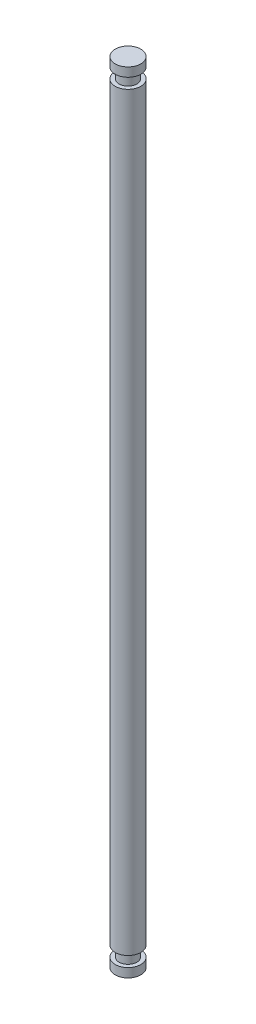
SolidWorks part; units mm, degrees
ref_plane "Front Plane" through (0, 0, 0) normal (1, 0, 0) x (0, 1, 0)
ref_plane "Top Plane" through (0, 0, 0) normal (0, 0, 1) x (0, 1, 0)
ref_plane "Right Plane" through (0, 0, 0) normal (0, 1, 0) x (-1, 0, 0)
sketch "Sketch1" plane through (0, 0, 0) normal (0, 0, 1) x (0, 1, 0)
  line L0 (-976.376, 0) -> (-976.376, 31.7309)
  line L1 (-976.376, 31.7309) -> (-954.024, 31.7309)
  line L2 (-954.024, 31.7309) -> (-954.024, 22.0218)
  line L3 (-954.024, 22.0218) -> (-928.2176, 22.0218)
  line L4 (-928.2176, 22.0218) -> (-928.2176, 31.7309)
  line L5 (-928.2176, 31.7309) -> (928.3446, 31.7309)
  line L6 (928.3446, 31.7309) -> (928.3446, 22.0218)
  line L7 (928.3446, 22.0218) -> (954.151, 22.0218)
  line L8 (954.151, 22.0218) -> (954.151, 31.7309)
  line L9 (954.151, 31.7309) -> (976.376, 31.7309)
  line L10 (976.376, 31.7309) -> (976.376, 0)
  line L11 (976.376, 0) -> (-976.376, 0)
  line L12 (-1001.776, 0) -> (1001.776, 0) construction
revolve "Revolve1" add sketch "Sketch1" angle 360 about L12
sketch "Sketch2" plane through (0, 0, 0) normal (0, 1, 0) x (-1, 0, 0)
  line L1 (24.6062, -6.35) -> (88.0682, -6.35)
  line L2 (24.6062, -6.35) -> (24.6062, 6.35)
  line L3 (24.6062, 6.35) -> (88.0682, 6.35)
  line L4 (88.0682, -6.35) -> (88.0682, 6.35)
extrude "Cut-Extrude2" cut sketch "Sketch2" along normal blind 1856.5622 from offset 928.2176
